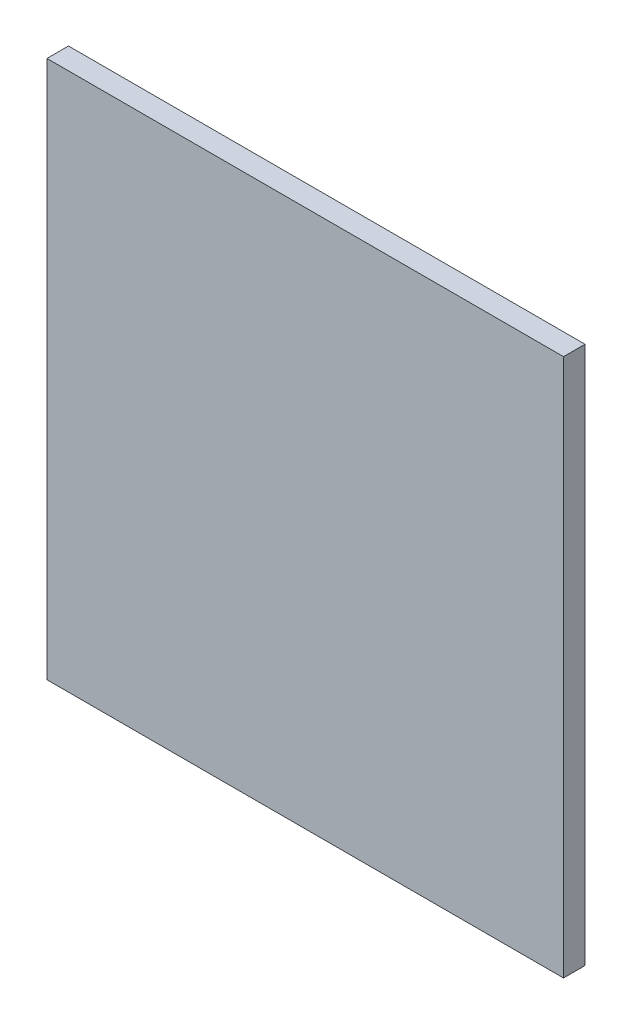
SolidWorks part; units mm, degrees
ref_plane "Plan de face" through (0, 0, 0) normal (0, 0, 1) x (1, 0, 0)
ref_plane "Plan de dessus" through (0, 0, 0) normal (0, 1, 0) x (1, 0, 0)
ref_plane "Plan de droite" through (0, 0, 0) normal (1, 0, 0) x (0, 0, -1)
sketch "Esquisse1" plane through (0, 0, 0) normal (0, 0, 1) x (1, 0, 0)
  line L1 (-240, 250) -> (240, 250)
  line L2 (-240, 250) -> (-240, -250)
  line L3 (-240, -250) -> (240, -250)
  line L4 (240, 250) -> (240, -250)
  line L5 (-240, 250) -> (240, -250) construction
  line L6 (-240, -250) -> (240, 250) construction
  point P0 (0, 0)
  dimension "D1" = 480
  dimension "D2" = 500
extrude "Boss.-Extru.1" add sketch "Esquisse1" along normal blind 20
